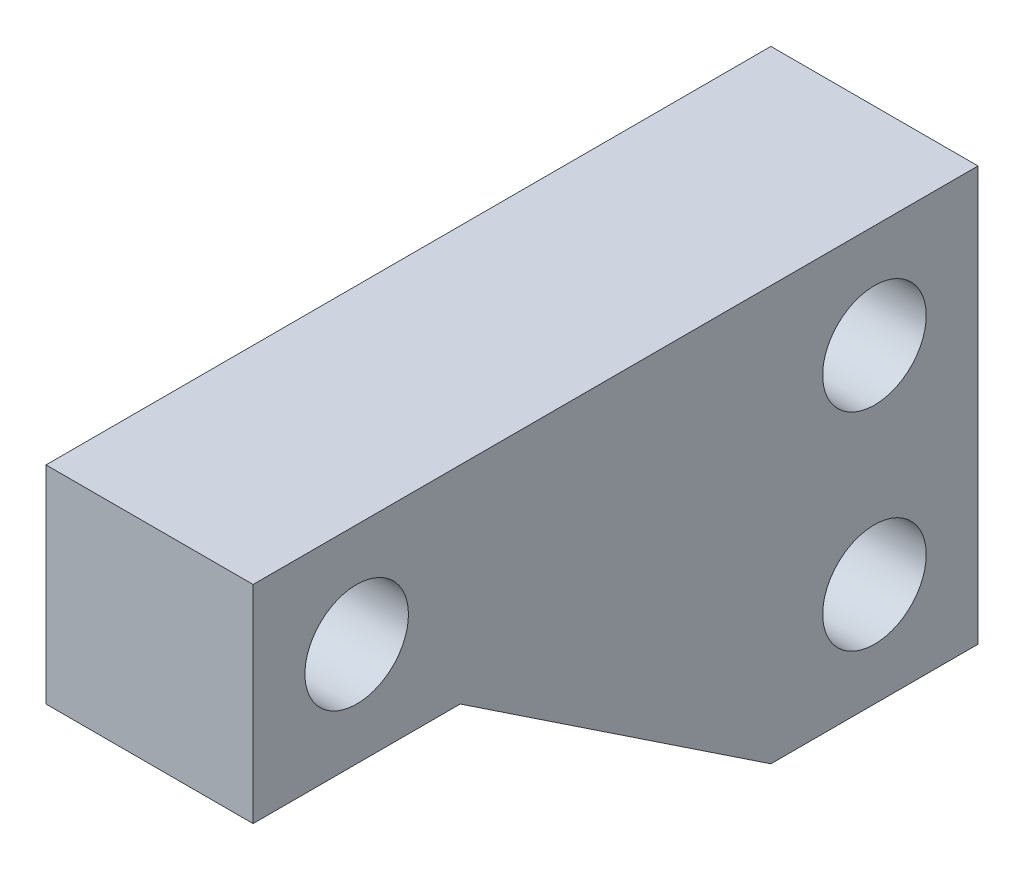
SolidWorks part; units mm, degrees
ref_plane "Plan de face" through (0, 0, 0) normal (0, 0, 1) x (1, 0, 0)
ref_plane "Plan de dessus" through (0, 0, 0) normal (0, 1, 0) x (1, 0, 0)
ref_plane "Plan de droite" through (0, 0, 0) normal (1, 0, 0) x (0, 0, -1)
sketch "Esquisse2" plane through (0, 0, 0) normal (1, 0, 0) x (0, 0, -1)
  line L0 (-42.2464, -6.4857) -> (-42.2464, 3.5143) construction
  line L1 (-47.2464, 3.5143) -> (-12.2464, 3.5143)
  line L2 (-47.2464, 3.5143) -> (-47.2464, -6.4857)
  line L3 (-22.2464, -16.4857) -> (-12.2464, -16.4857)
  line L4 (-12.2464, 3.5143) -> (-12.2464, -16.4857)
  line L5 (-47.2464, 3.5143) -> (-37.2464, 3.5143)
  line L6 (-47.2464, 3.5143) -> (-47.2464, -6.4857)
  line L7 (-47.2464, -6.4857) -> (-37.2464, -6.4857)
  line L8 (-37.2464, 3.5143) -> (-37.2464, -6.4857)
  line L9 (-37.2464, -1.4857) -> (-47.2464, -1.4857) construction
  line L10 (-47.2464, -1.4857) -> (-12.2464, -1.4857) construction
  line L11 (-12.2464, 3.5143) -> (-22.2464, -16.4857) construction
  line L12 (-12.2464, 3.5143) -> (-22.2464, 3.5143)
  line L13 (-12.2464, 3.5143) -> (-12.2464, -16.4857)
  line L14 (-12.2464, -16.4857) -> (-22.2464, -16.4857)
  line L15 (-22.2464, 3.5143) -> (-22.2464, -16.4857)
  line L16 (-22.2464, 3.5143) -> (-12.2464, -16.4857) construction
  line L17 (-22.2464, -6.4857) -> (-12.2464, -6.4857) construction
  line L18 (-17.2464, -16.4857) -> (-17.2464, 3.5143) construction
  line L19 (-17.2464, -6.4857) -> (-17.2464, -11.4857) construction
  line L20 (-37.2464, -6.4857) -> (-22.2464, -16.4857)
  circle A0 centre (-42.2464, -1.4857) radius 2.5
  circle A1 centre (-17.2464, -1.4857) radius 2.5
  circle A2 centre (-17.2464, -11.4857) radius 2.5
  dimension "D6" = 5
  dimension "D1" = 35
  dimension "D2" = 20
  dimension "D3" = 10
  dimension "D4" = 10
  dimension "D5" = 10
extrude "Boss.-Extru.3" add sketch "Esquisse2" along normal blind 10 contours L8 L20 L15 L1 | L8 L1 L2 L7 A0 | L1 L15 L3 L4 A2 A1
